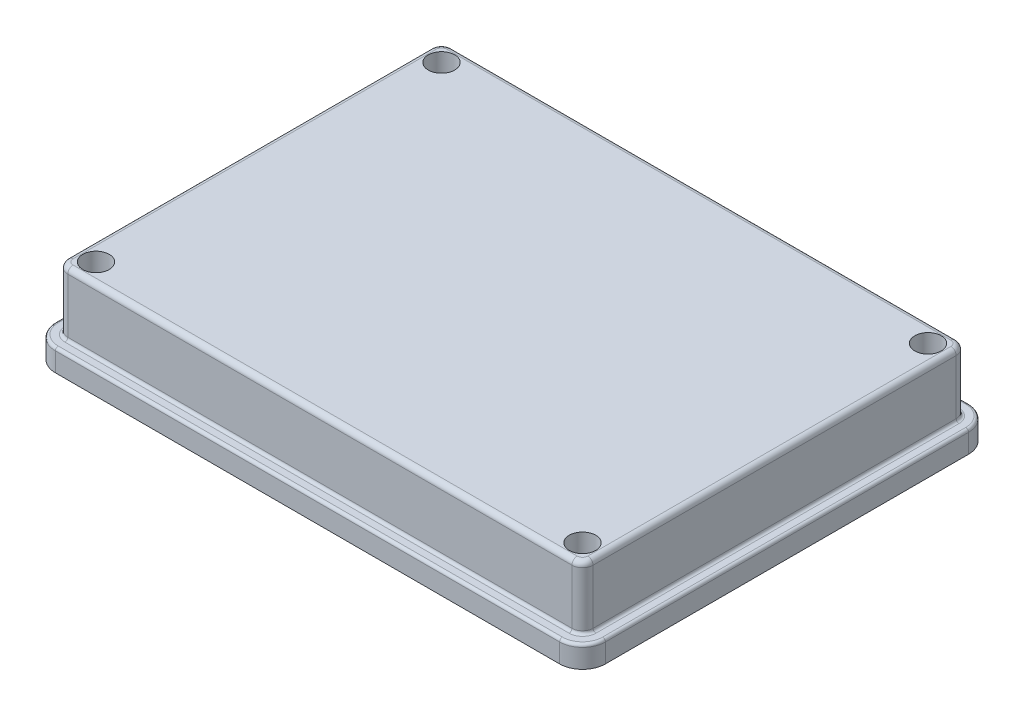
SolidWorks part; units mm, degrees
material "PBT General Purpose"
ref_plane "Front Plane" through (0, 0, 0) normal (0, 0, 1) x (1, 0, 0)
ref_plane "Top Plane" through (0, 0, 0) normal (0, 1, 0) x (1, 0, 0)
ref_plane "Right Plane" through (0, 0, 0) normal (1, 0, 0) x (0, 0, -1)
sketch "Sketch1" plane through (0, 0, 0) normal (0, 1, 0) x (1, 0, 0)
  line L0 (0, 54.5) -> (0, 0) construction
  line L1 (0, 0) -> (74.5, 0) construction
  line L2 (74.5, -51.5) -> (74.5, 51.5)
  line L3 (-71.5, 54.5) -> (71.5, 54.5)
  line L4 (-74.5, -51.5) -> (-74.5, 51.5)
  line L5 (-71.5, -54.5) -> (71.5, -54.5)
  arc A0 (74.5, 51.5) -> (71.5, 54.5) centre (71.5, 51.5) ccw
  arc A1 (-74.5, 51.5) -> (-71.5, 54.5) centre (-71.5, 51.5) cw
  arc A2 (-74.5, -51.5) -> (-71.5, -54.5) centre (-71.5, -51.5) ccw
  arc A3 (74.5, -51.5) -> (71.5, -54.5) centre (71.5, -51.5) cw
  point P17 (-74.5, 0)
  dimension "D1" = 3
  dimension "D2" = 109
  dimension "D3" = 149
extrude "Boss-Extrude1" add sketch "Sketch1" along normal blind 24
fillet "Fillet1" radius 1.5 8 edges at (74.5, 24, 0) (73.6213, 24, 53.6213) (0, 24, 54.5) (-73.6213, 24, 53.6213) (-74.5, 24, 0) (-73.6213, 24, -53.6213) (0, 24, -54.5) (73.6213, 24, -53.6213)
shell "Shell1" thickness 2
sketch "Sketch2" plane through (0, 0, 0) normal (0, 1, 0) x (1, 0, 0)
  line L0 (72.5, -51.5) -> (72.5, 51.5) construction
  line L1 (-71.5, -52.5) -> (71.5, -52.5) construction
  line L2 (-72.5, 51.5) -> (-72.5, -51.5) construction
  line L3 (71.5, 52.5) -> (-71.5, 52.5) construction
  line L4 (72.5, -51.5) -> (72.5, 51.5)
  line L5 (-71.5, -52.5) -> (71.5, -52.5)
  line L6 (-72.5, 51.5) -> (-72.5, -51.5)
  line L7 (71.5, 52.5) -> (-71.5, 52.5)
  line L16 (-78, 51.5) -> (-78, -51.5)
  line L17 (-71.5, -58) -> (71.5, -58)
  line L18 (78, -51.5) -> (78, 51.5)
  line L19 (71.5, 58) -> (-71.5, 58)
  line L20 (-78, 51.5) -> (-78, -51.5)
  line L21 (-71.5, -58) -> (71.5, -58)
  line L22 (78, -51.5) -> (78, 51.5)
  line L23 (71.5, 58) -> (-71.5, 58)
  arc A0 (71.5, -52.5) -> (72.5, -51.5) centre (71.5, -51.5) ccw construction
  arc A1 (-72.5, -51.5) -> (-71.5, -52.5) centre (-71.5, -51.5) ccw construction
  arc A2 (-71.5, 52.5) -> (-72.5, 51.5) centre (-71.5, 51.5) ccw construction
  arc A3 (72.5, 51.5) -> (71.5, 52.5) centre (71.5, 51.5) ccw construction
  arc A4 (71.5, -52.5) -> (72.5, -51.5) centre (71.5, -51.5) ccw
  arc A5 (-72.5, -51.5) -> (-71.5, -52.5) centre (-71.5, -51.5) ccw
  arc A6 (-71.5, 52.5) -> (-72.5, 51.5) centre (-71.5, 51.5) ccw
  arc A7 (72.5, 51.5) -> (71.5, 52.5) centre (71.5, 51.5) ccw
  arc A16 (-71.5, 58) -> (-78, 51.5) centre (-71.5, 51.5) ccw
  arc A17 (-78, -51.5) -> (-71.5, -58) centre (-71.5, -51.5) ccw
  arc A18 (71.5, -58) -> (78, -51.5) centre (71.5, -51.5) ccw
  arc A19 (78, 51.5) -> (71.5, 58) centre (71.5, 51.5) ccw
  arc A20 (-71.5, 58) -> (-78, 51.5) centre (-71.5, 51.5) ccw
  arc A21 (-78, -51.5) -> (-71.5, -58) centre (-71.5, -51.5) ccw
  arc A22 (71.5, -58) -> (78, -51.5) centre (71.5, -51.5) ccw
  arc A23 (78, 51.5) -> (71.5, 58) centre (71.5, 51.5) ccw
  dimension "D1" = 3.5
extrude "Boss-Extrude2" add sketch "Sketch2" along normal blind 6.2
sketch "Sketch3" plane through (0, 0, 0) normal (0, -1, 0) x (1, 0, 0)
  line L12 (-71.5, -56.5) -> (71.5, -56.5)
  line L13 (76.5, -51.5) -> (76.5, 51.5)
  line L14 (71.5, 56.5) -> (-71.5, 56.5)
  line L15 (-76.5, 51.5) -> (-76.5, -51.5)
  line L16 (-71.5, -56.5) -> (71.5, -56.5)
  line L17 (76.5, -51.5) -> (76.5, 51.5)
  line L18 (71.5, 56.5) -> (-71.5, 56.5)
  line L19 (-76.5, 51.5) -> (-76.5, -51.5)
  line L33 (74, -51.5) -> (74, 51.5)
  line L34 (-71.5, -54) -> (71.5, -54)
  line L35 (-74, 51.5) -> (-74, -51.5)
  line L36 (71.5, 54) -> (-71.5, 54)
  line L37 (74, -51.5) -> (74, 51.5)
  line L38 (-71.5, -54) -> (71.5, -54)
  line L39 (-74, 51.5) -> (-74, -51.5)
  line L40 (71.5, 54) -> (-71.5, 54)
  arc A12 (-76.5, -51.5) -> (-71.5, -56.5) centre (-71.5, -51.5) ccw
  arc A13 (71.5, -56.5) -> (76.5, -51.5) centre (71.5, -51.5) ccw
  arc A14 (76.5, 51.5) -> (71.5, 56.5) centre (71.5, 51.5) ccw
  arc A15 (-71.5, 56.5) -> (-76.5, 51.5) centre (-71.5, 51.5) ccw
  arc A16 (-76.5, -51.5) -> (-71.5, -56.5) centre (-71.5, -51.5) ccw
  arc A17 (71.5, -56.5) -> (76.5, -51.5) centre (71.5, -51.5) ccw
  arc A18 (76.5, 51.5) -> (71.5, 56.5) centre (71.5, 51.5) ccw
  arc A19 (-71.5, 56.5) -> (-76.5, 51.5) centre (-71.5, 51.5) ccw
  arc A32 (71.5, -54) -> (74, -51.5) centre (71.5, -51.5) ccw
  arc A33 (-74, -51.5) -> (-71.5, -54) centre (-71.5, -51.5) ccw
  arc A34 (-71.5, 54) -> (-74, 51.5) centre (-71.5, 51.5) ccw
  arc A35 (74, 51.5) -> (71.5, 54) centre (71.5, 51.5) ccw
  arc A36 (71.5, -54) -> (74, -51.5) centre (71.5, -51.5) ccw
  arc A37 (-74, -51.5) -> (-71.5, -54) centre (-71.5, -51.5) ccw
  arc A38 (-71.5, 54) -> (-74, 51.5) centre (-71.5, 51.5) ccw
  arc A39 (74, 51.5) -> (71.5, 54) centre (71.5, 51.5) ccw
  dimension "D1" = 1.5
  dimension "D2" = 1.5
extrude "Cut-Extrude1" cut sketch "Sketch3" against normal blind 5
fillet "Fillet2" radius 0.8 16 edges at (0, 6.2, -54.5) (-73.6213, 6.2, -53.6213) (-74.5, 6.2, 0) (-73.6213, 6.2, 53.6213) (0, 6.2, 54.5) (73.6213, 6.2, 53.6213) (74.5, 6.2, 0) (73.6213, 6.2, -53.6213) (0, 6.2, -58) (76.0962, 6.2, -56.0962) (78, 6.2, 0) (76.0962, 6.2, 56.0962) (0, 6.2, 58) (-76.0962, 6.2, 56.0962) (-78, 6.2, 0) (-76.0962, 6.2, -56.0962)
sketch "Sketch4" plane through (0, 24, 0) normal (0, 1, 0) x (1, 0, 0)
  line L0 (0, 91.6854) -> (0, 0) construction
  line L1 (0, 0) -> (117.8157, 0) construction
  circle A0 centre (69, 49) radius 5
  circle A1 centre (69, -49) radius 5
  circle A2 centre (-69, 49) radius 5
  circle A3 centre (-69, -49) radius 5
  dimension "D1" = 10
  dimension "D2" = 138
  dimension "D3" = 98
extrude "Boss-Extrude4" add sketch "Sketch4" against normal up to surface (23 mm away) from offset 1 up to face at (0, 0, 0) offset against normal yes
hole_wizard "CBORE for M5 Hex Head Bolt1" positions "Sketch6" profile "Sketch5" counterbore size "M5" standard "ISO" end condition through all
sketch "Sketch6" plane through (0, 24, 0) normal (0, 1, 0) x (1, 0, 0)
  point P0 (-69, -49)
  point P3 (69, -49)
  point P6 (-69, 49)
  point P9 (69, 49)
sketch "Sketch5" plane through (-69, 24, 49) normal (1, 0, 0) x (0, 0, 1)
  line L0 (0, 0) -> (0, 24)
  line L1 (0, 24) -> (1.85, 24)
  line L3 (1.85, 24) -> (1.85, 12)
  line L4 (1.85, 12) -> (3.75, 12)
  line L5 (3.75, 12) -> (3.75, 0)
  line L7 (3.75, 0) -> (0, 0)
  line L11 (0, -6.35) -> (0, 107.95) construction
  dimension "Thru Hole Dia." = 3.7
  dimension "Thru Hole Depth" = 24
  dimension "C'Bore Dia." = 7.5
  dimension "C'Bore Depth" = 12
